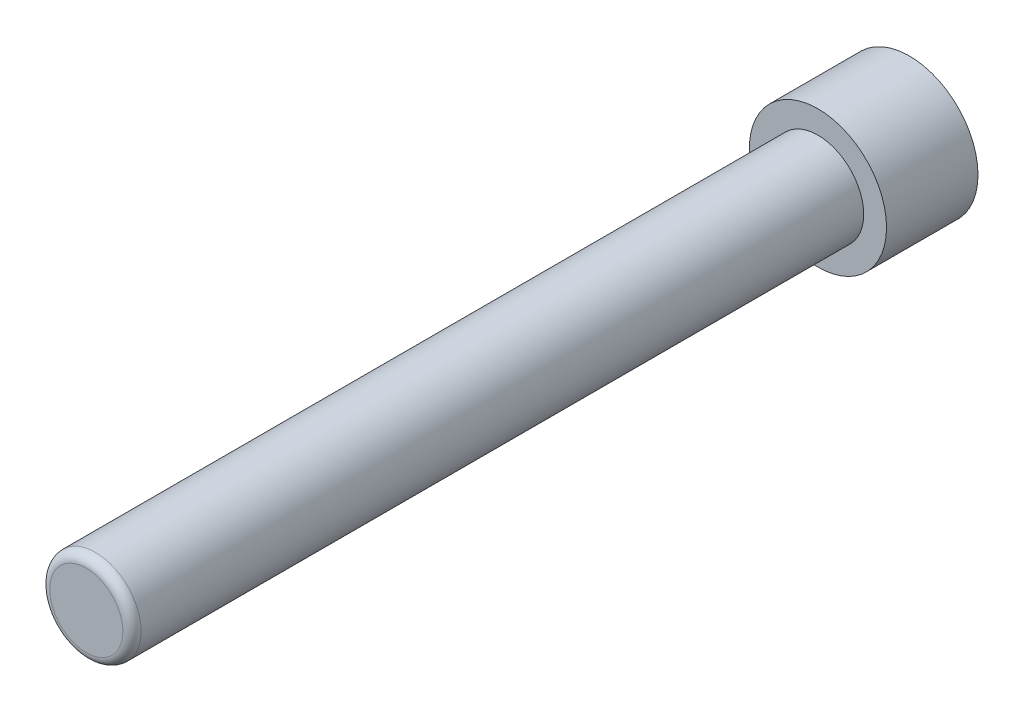
SolidWorks part; units mm, degrees
ref_plane "Front Plane" through (0, 0, 0) normal (0, 0, 1) x (1, 0, 0)
ref_plane "Top Plane" through (0, 0, 0) normal (0, 1, 0) x (1, 0, 0)
ref_plane "Right Plane" through (0, 0, 0) normal (1, 0, 0) x (0, 0, -1)
sketch "Sketch1" plane through (0, 0, 0) normal (0, 0, 1) x (1, 0, 0)
  circle A0 centre (0, 0) radius 19.05
extrude "Boss-Extrude1" add sketch "Sketch1" along normal blind 25.4
sketch "Sketch2" plane through (0, 0, 25.4) normal (0, 0, 1) x (1, 0, 0)
  circle A0 centre (0, 0) radius 12.7
extrude "Boss-Extrude2" add sketch "Sketch2" along normal blind 203.2
fillet "Fillet1" radius 2.54 1 edges at (12.7, 0, 228.6)
